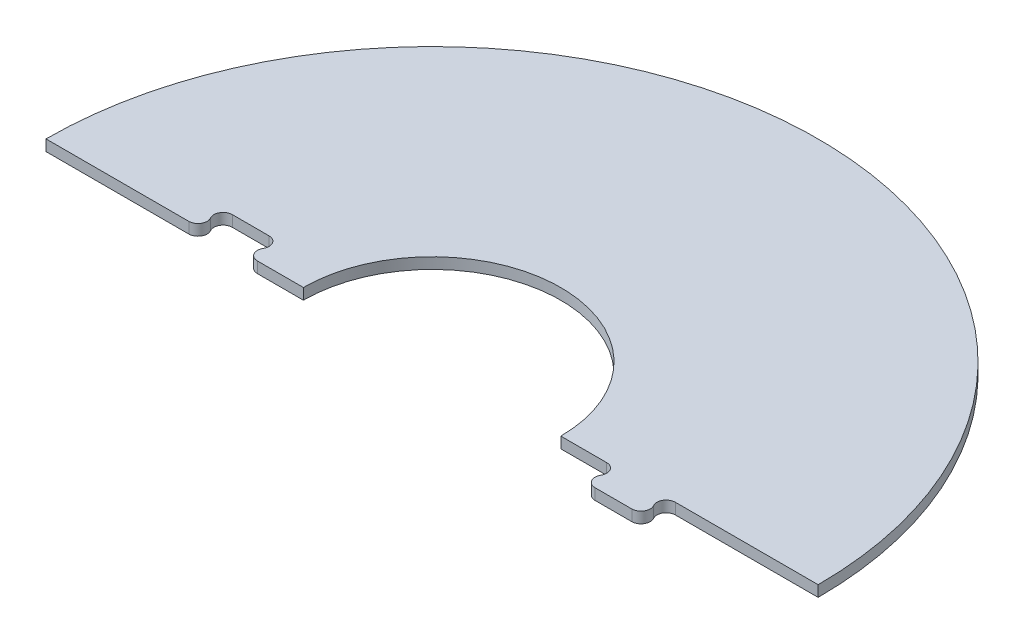
SolidWorks part; units mm, degrees
ref_plane "Front Plane" through (0, 0, 0) normal (0, 0, 1) x (1, 0, 0)
ref_plane "Top Plane" through (0, 0, 0) normal (0, 1, 0) x (1, 0, 0)
ref_plane "Right Plane" through (0, 0, 0) normal (1, 0, 0) x (0, 0, -1)
sketch "Sketch1" plane through (0, 0, 0) normal (0, 1, 0) x (1, 0, 0)
  line L0 (-420, 0) -> (-264.641, 0)
  line L1 (190, 0) -> (140, 0)
  line L2 (-190, 0) -> (-140, 0)
  line L3 (207.3205, -30) -> (247.3205, -30)
  line L4 (-207.3205, 30) -> (-247.3205, 30)
  line L5 (420, 0) -> (264.641, 0)
  arc A0 (140, 0) -> (-140, 0) centre (0, 0) ccw
  arc A1 (420, 0) -> (-420, 0) centre (0, 0) ccw
  arc A2 (-190, 0) -> (-198.6603, 15) centre (-190, 10) cw
  arc A3 (-207.3205, 30) -> (-198.6603, 15) centre (-207.3205, 20) cw
  arc A4 (-255.9808, 15) -> (-264.641, 0) centre (-264.641, 10) cw
  arc A6 (190, 0) -> (198.6603, -15) centre (190, -10) cw
  arc A7 (207.3205, -30) -> (198.6603, -15) centre (207.3205, -20) cw
  arc A8 (-247.3205, 30) -> (-255.9808, 15) centre (-247.3205, 20) ccw
  arc A9 (247.3205, -30) -> (255.9808, -15) centre (247.3205, -20) ccw
  arc A10 (255.9808, -15) -> (264.641, 0) centre (264.641, -10) cw
  point P25 (0, 0)
  point P35 (0, 0)
  dimension "D1" = 420
  dimension "D2" = 140
  dimension "D3" = 10
  dimension "D7" = 40
  dimension "D4" = 50
  dimension "D5" = 30
  dimension "D6" = 2
extrude "Boss-Extrude1" add sketch "Sketch1" along normal blind 12
